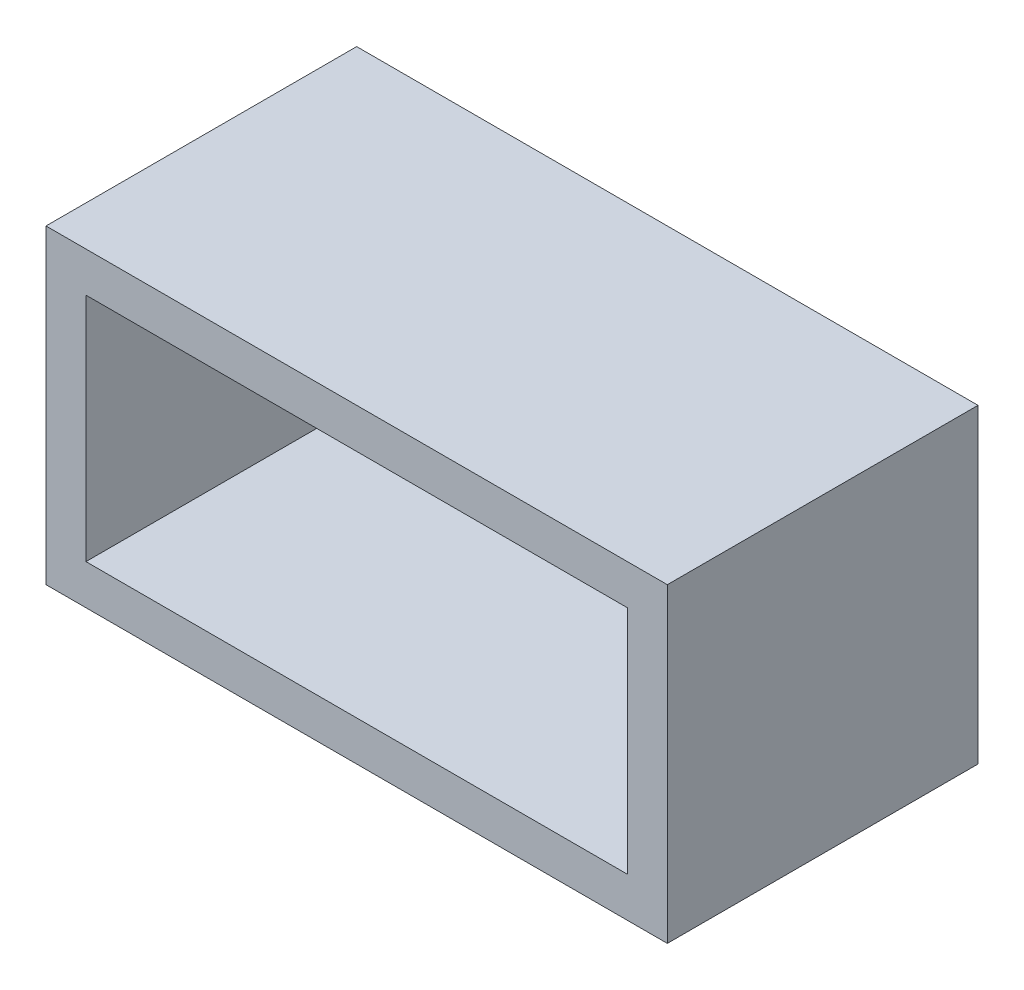
SolidWorks part; units mm, degrees
ref_plane "Front Plane" through (0, 0, 0) normal (0, 0, 1) x (1, 0, 0)
ref_plane "Top Plane" through (0, 0, 0) normal (0, 1, 0) x (1, 0, 0)
ref_plane "Right Plane" through (0, 0, 0) normal (1, 0, 0) x (0, 0, -1)
sketch "Soft_contact_and_wrap_profile" plane through (0, 0, 0) normal (0, 0, 1) x (1, 0, 0)
  line L1 (14, -21) -> (28, -21)
  line L2 (14, -21) -> (14, -14)
  line L3 (14, -14) -> (28, -14)
  line L4 (28, -21) -> (28, -14)
  dimension "D1" = 14
  dimension "D2" = 7
extrude "Soft_contact_and_wrap" add sketch "Soft_contact_and_wrap_profile" along normal blind 7 from offset 1
sketch "Finger_slip_pocket_profile" plane through (0, 0, 0) normal (0, 0, 1) x (1, 0, 0)
  line L1 (14.9, -20.1) -> (27.1, -20.1)
  line L2 (14.9, -20.1) -> (14.9, -14.9)
  line L3 (14.9, -14.9) -> (27.1, -14.9)
  line L4 (27.1, -20.1) -> (27.1, -14.9)
  dimension "D1" = 12.2
  dimension "D2" = 5.2
extrude "Open_top_slip_pocket" cut sketch "Finger_slip_pocket_profile" along normal blind 7
sketch "Pad_capture_M2_profile" plane through (0, 0, 0) normal (0, 0, 1) x (1, 0, 0)
  circle A0 centre (18, -17.5) radius 1.1
  circle A1 centre (24, -17.5) radius 1.1
  dimension "D1" = 2.2
  dimension "D2" = 2.2
extrude "Pad_capture_M2" cut sketch "Pad_capture_M2_profile" along normal through all from offset 50
